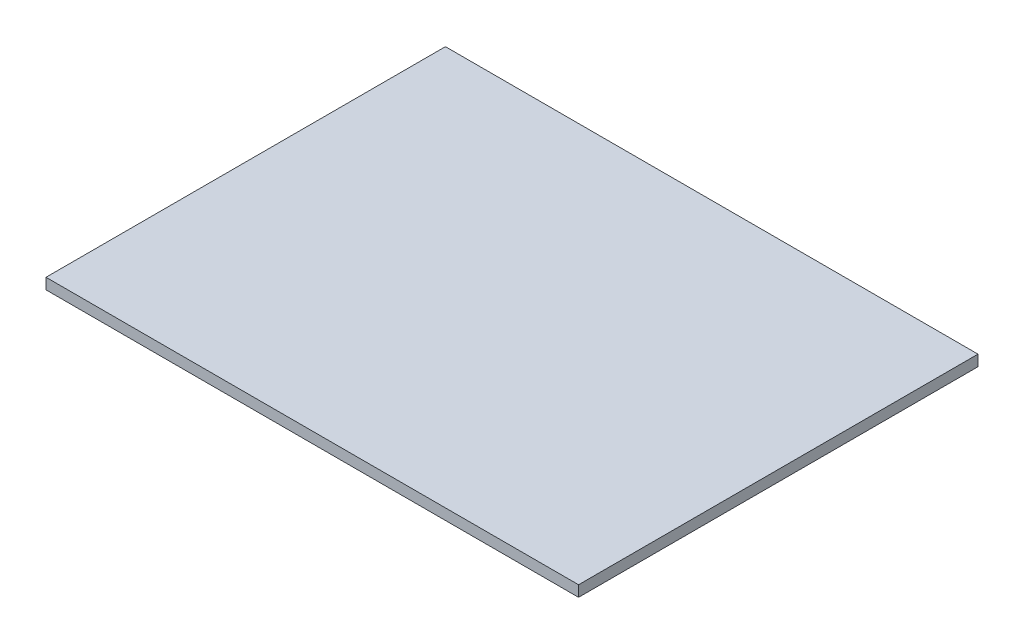
SolidWorks part; units mm, degrees
ref_plane "Front Plane" through (0, 0, 0) normal (0, 0, 1) x (1, 0, 0)
ref_plane "Top Plane" through (0, 0, 0) normal (0, 1, 0) x (1, 0, 0)
ref_plane "Right Plane" through (0, 0, 0) normal (1, 0, 0) x (0, 0, -1)
sketch "Sketch1" plane through (0, 0, 0) normal (0, 1, 0) x (1, 0, 0)
  line L1 (122, -91.5) -> (-122, -91.5)
  line L2 (122, -91.5) -> (122, 91.5)
  line L3 (122, 91.5) -> (-122, 91.5)
  line L4 (-122, -91.5) -> (-122, 91.5)
  line L5 (122, -91.5) -> (-122, 91.5) construction
  line L6 (122, 91.5) -> (-122, -91.5) construction
  point P0 (0, 0)
  dimension "D1" = 244
  dimension "D2" = 183
extrude "Boss-Extrude1" add sketch "Sketch1" along normal blind 5
